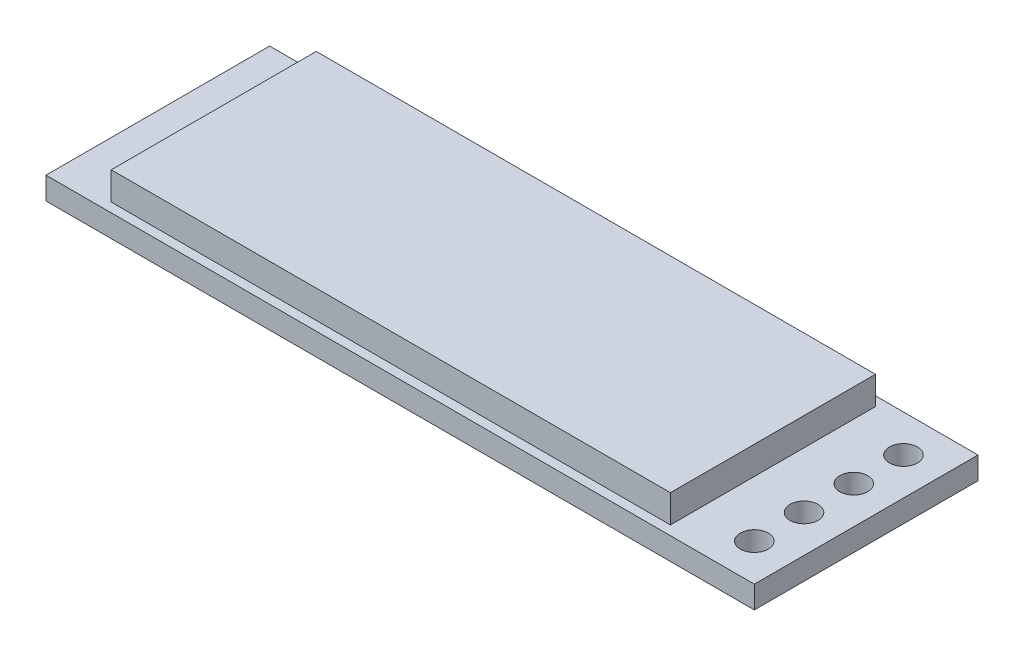
SolidWorks part; units mm, degrees
ref_plane "Спереди" through (0, 0, 0) normal (0, 0, 1) x (1, 0, 0)
ref_plane "Сверху" through (0, 0, 0) normal (0, 1, 0) x (1, 0, 0)
ref_plane "Справа" through (0, 0, 0) normal (1, 0, 0) x (0, 0, -1)
sketch "Эскиз1" plane through (0, 0, 0) normal (0, 1, 0) x (1, 0, 0)
  line L1 (0, 6) -> (-38, 6)
  line L2 (0, 6) -> (0, -6)
  line L3 (0, -6) -> (-38, -6)
  line L4 (-38, 6) -> (-38, -6)
  dimension "D1" = 12
  dimension "D2" = 38
extrude "Бобышка-Вытянуть1" add sketch "Эскиз1" along normal blind 1.2
sketch "Эскиз2" plane through (0, 0, 0) normal (0, 1, 0) x (1, 0, 0)
  line L1 (-5, 5.5) -> (-35, 5.5)
  line L2 (-5, 5.5) -> (-5, -5.5)
  line L3 (-5, -5.5) -> (-35, -5.5)
  line L4 (-35, 5.5) -> (-35, -5.5)
  line L5 (-38, 6) -> (-38, -6) construction
  line L6 (0, 0) -> (-5, 0) construction
  dimension "D1" = 11
  dimension "D2" = 35
  dimension "D3" = 33
extrude "Бобышка-Вытянуть2" add sketch "Эскиз2" along normal blind 2.7
sketch "Эскиз3" plane through (0, 0, 0) normal (0, 1, 0) x (1, 0, 0)
  line L0 (-2, 1.3333) -> (-2, -1.3333) construction
  line L1 (-2, 0) -> (0, 0) construction
  line L2 (0, 6) -> (-38, 6) construction
  line L3 (0, -6) -> (0, 6) construction
  circle A0 centre (-2, 4) radius 0.75
  circle A1 centre (-2, 1.3333) radius 0.75
  circle A2 centre (-2, -1.3333) radius 0.75
  circle A3 centre (-2, -4) radius 0.75
  dimension "D2" = 1.5
  dimension "D3" = 2
  dimension "D4" = 2
  dimension "D1" = 4
extrude "Вырез-Вытянуть2" cut sketch "Эскиз3" along normal through all
sketch "Эскиз4" plane through (0, 0, 0) normal (0, 1, 0) x (1, 0, 0)
  line L0 (-38, 6) -> (-38, -6) construction
  line L1 (-24, -5) -> (-22, -5)
  line L2 (-24, -5) -> (-24, 5)
  line L3 (-24, 5) -> (-22, 5)
  line L4 (-22, -5) -> (-22, 5)
  line L5 (0, 0) -> (-24, 0) construction
  line L6 (-17, -5) -> (-15, -5)
  line L7 (-17, -5) -> (-17, 5)
  line L8 (-17, 5) -> (-15, 5)
  line L9 (-15, -5) -> (-15, 5)
  line L10 (0, -6) -> (0, 6) construction
  line L11 (-38, -6) -> (0, -6) construction
  line L13 (-11.3273, 1.2331) -> (-9.3273, 1.2331)
  line L14 (-11.3273, 1.2331) -> (-11.3273, 2.6033)
  line L15 (-11.3273, 2.6033) -> (-9.3273, 2.6033)
  line L16 (-9.3273, 1.2331) -> (-9.3273, 2.6033)
  point P14 (-15, 0)
  dimension "D1" = 16
  dimension "D2" = 2
  dimension "D3" = 23
  dimension "D4" = 1
extrude "Бобышка-Вытянуть3" add sketch "Эскиз4" against normal blind 2 from surface at 1.2 starting at face at (-2, 1.2, -4.75)
